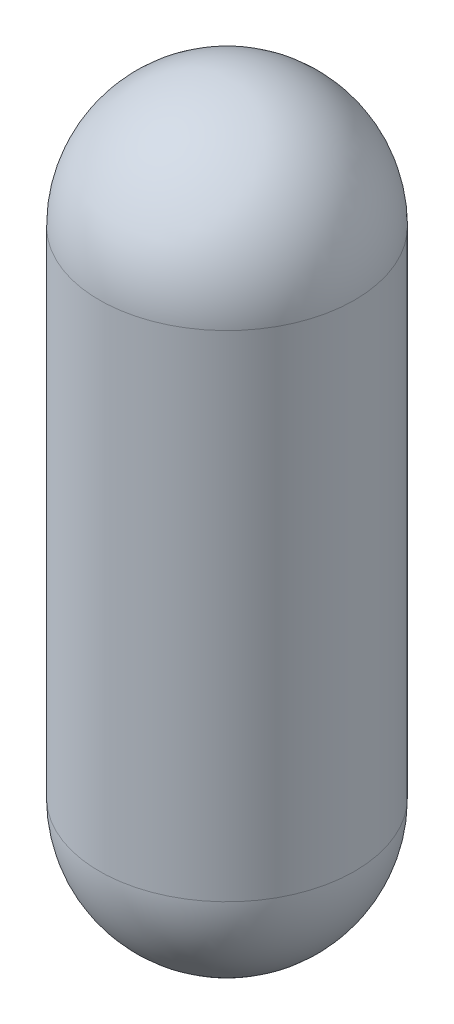
SolidWorks part; units mm, degrees
ref_plane "Front Plane" through (0, 0, 0) normal (0, 0, 1) x (1, 0, 0)
ref_plane "Top Plane" through (0, 0, 0) normal (0, 1, 0) x (1, 0, 0)
ref_plane "Right Plane" through (0, 0, 0) normal (1, 0, 0) x (0, 0, -1)
sketch "Sketch1" plane through (0, 0, 0) normal (0, 0, 1) x (1, 0, 0)
  line L0 (0, 0) -> (-163.83, 0) construction
  line L1 (0, 0) -> (0, 481.33) construction
  line L2 (163.83, 317.5) -> (185.2243, 317.5) construction
  line L3 (-163.83, -317.5) -> (-163.83, 317.5)
  line L5 (0, 481.33) -> (0, -481.33)
  arc A0 (0, 481.33) -> (-163.83, 317.5) centre (0, 317.5) ccw
  arc A1 (0, -481.33) -> (-163.83, -317.5) centre (0, -317.5) cw
  point P10 (163.83, 0)
  dimension "D1" = 163.83
  dimension "D2" = 481.33
  dimension "D3" = 163.83
revolve "Revolve1" add sketch "Sketch1" angle 360 about L5
